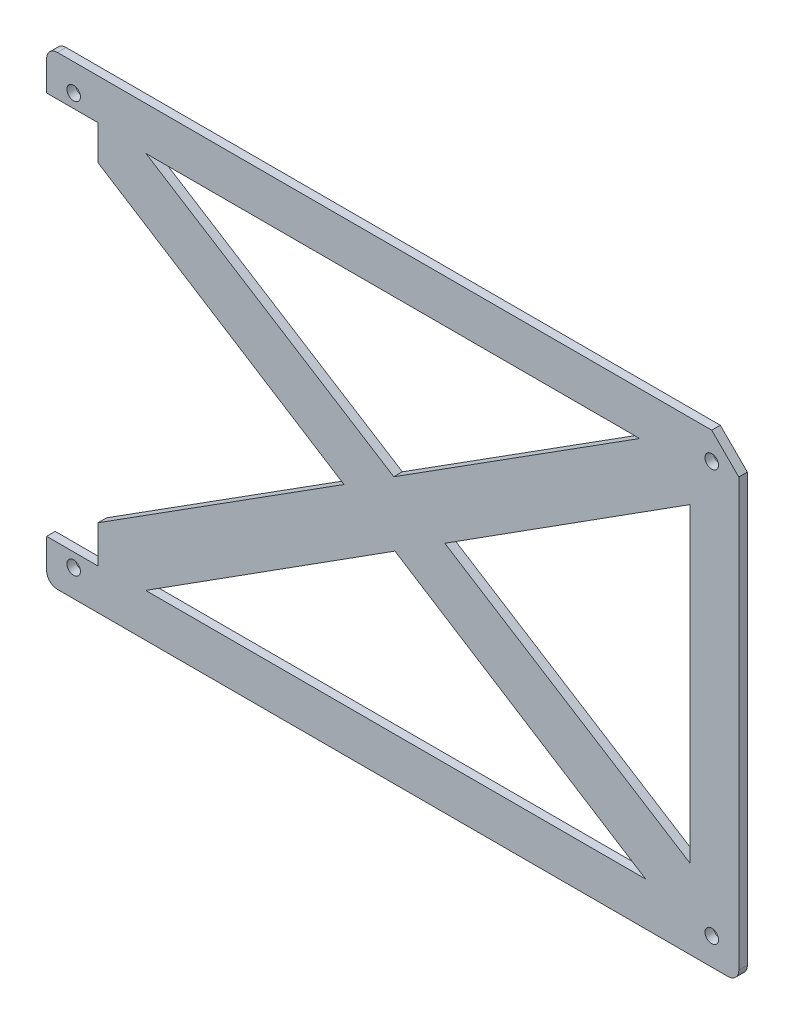
SolidWorks part; units mm, degrees
ref_plane "Front Plane" through (0, 0, 0) normal (0, 0, 1) x (1, 0, 0)
ref_plane "Top Plane" through (0, 0, 0) normal (0, 1, 0) x (1, 0, 0)
ref_plane "Right Plane" through (0, 0, 0) normal (1, 0, 0) x (0, 0, -1)
sketch "Sketch2" plane through (0, 0, 0) normal (0, 0, 1) x (1, 0, 0)
  line L0 (64, -41) -> (64, 38)
  line L1 (-62, -43) -> (62, -43)
  line L2 (-64, 41) -> (-64, 35.5)
  line L3 (59, 43) -> (-62, 43)
  line L4 (64, 38) -> (59, 43)
  line L5 (-54.5, 35.5) -> (52.8916, -32.1266) construction
  line L6 (-45.6242, 35) -> (45.6673, 35)
  line L7 (-45.6812, -35) -> (46.77, -35)
  line L8 (55, 29.0865) -> (55, -28.365)
  line L9 (55.6573, 35.3848) -> (5.2619, 2.956) construction
  line L10 (-54.5, 29.0865) -> (-9.0091, 0.2986)
  line L11 (45.6673, 35) -> (0.2002, 6.1435)
  line L12 (-45.6242, 35) -> (0.2002, 6.1435)
  line L13 (55, 29.0865) -> (9.6285, 0.2063)
  line L14 (-9.0091, 0.2986) -> (-54.5, -28.573)
  line L15 (-3.8961, -2.9371) -> (-54.5, -35.5) construction
  line L16 (0.4096, -5.6618) -> (-45.6812, -35)
  line L17 (9.6285, 0.2063) -> (55, -28.365)
  line L18 (0.4096, -5.6618) -> (46.77, -35)
  line L19 (-64, 35.5) -> (-54.5, 35.5)
  line L20 (-54.5, 35.5) -> (-54.5, 29.0865)
  line L21 (-54.5, -28.573) -> (-54.5, -35.5)
  line L22 (-54.5, -35.5) -> (-64, -35.5)
  line L23 (-64, -35.5) -> (-64, -41)
  circle A0 centre (59, -38) radius 1.25
  arc A1 (62, -43) -> (64, -41) centre (62, -41) ccw
  circle A2 centre (-59, -38) radius 1.25
  arc A3 (-64, -41) -> (-62, -43) centre (-62, -41) ccw
  arc A4 (-62, 43) -> (-64, 41) centre (-62, 41) ccw
  circle A5 centre (59, 38) radius 1.25
  circle A6 centre (-59, 38) radius 1.25
  dimension "D6" = 2.5
  dimension "D1" = 8
  dimension "D2" = 9
  dimension "D3" = 8
  dimension "D4" = 71
  dimension "D5" = 9.5
  dimension "D21" = 35.5
  dimension "D32" = 38
extrude "Boss-Extrude1" add sketch "Sketch2" along normal blind 1.5875
